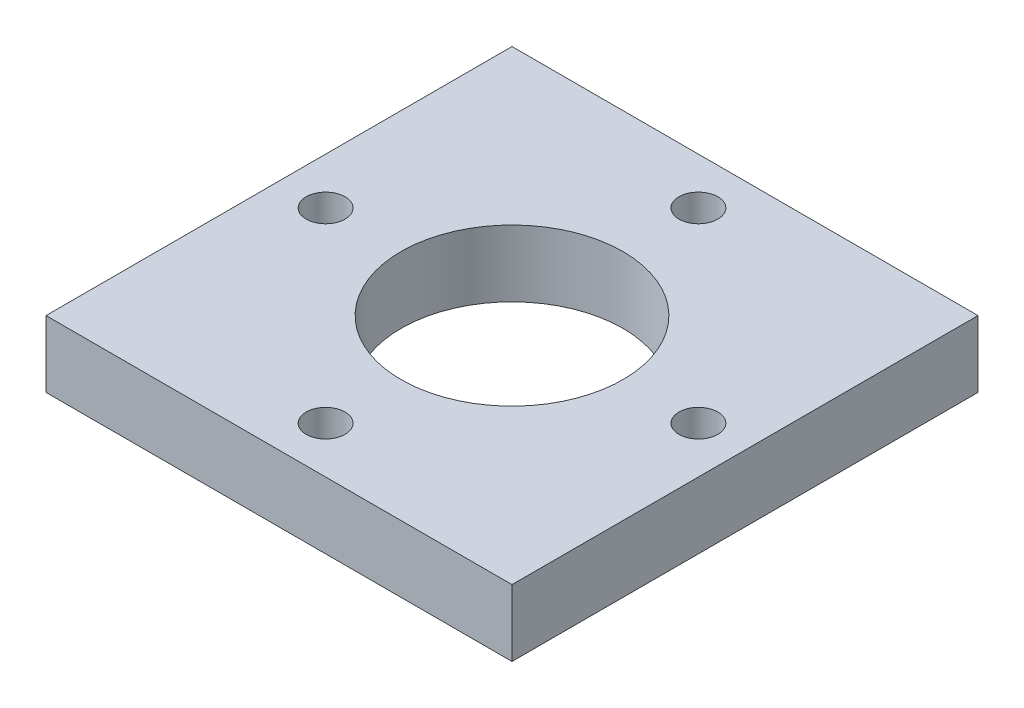
SolidWorks part; units mm, degrees
material "AISI 1020"
ref_plane "Front Plane" through (0, 0, 0) normal (0, 0, 1) x (1, 0, 0)
ref_plane "Top Plane" through (0, 0, 0) normal (0, 1, 0) x (1, 0, 0)
ref_plane "Right Plane" through (0, 0, 0) normal (1, 0, 0) x (0, 0, -1)
sketch "Sketch1" plane through (0, 0, 0) normal (0, 1, 0) x (1, 0, 0)
  line L1 (-33.3375, -33.3375) -> (33.3375, -33.3375)
  line L2 (-33.3375, -33.3375) -> (-33.3375, 33.3375)
  line L3 (-33.3375, 33.3375) -> (33.3375, 33.3375)
  line L4 (33.3375, -33.3375) -> (33.3375, 33.3375)
  line L5 (-33.3375, -33.3375) -> (33.3375, 33.3375) construction
  line L6 (-33.3375, 33.3375) -> (33.3375, -33.3375) construction
  circle A0 centre (0, 0) radius 15.875
  circle A1 centre (0, 26.67) radius 2.7788
  circle A2 centre (26.67, 0) radius 2.7788
  circle A3 centre (0, -26.67) radius 2.7788
  circle A4 centre (-26.67, 0) radius 2.7788
  point P0 (0, 0)
  point P19 (0, 0)
  dimension "D3" = 31.75
  dimension "D4" = 26.67
  dimension "D5" = 5.5575
  dimension "D1" = 66.675
  dimension "D2" = 66.675
  dimension "D6" = 4
extrude "Boss-Extrude1" add sketch "Sketch1" along normal blind 9.525
